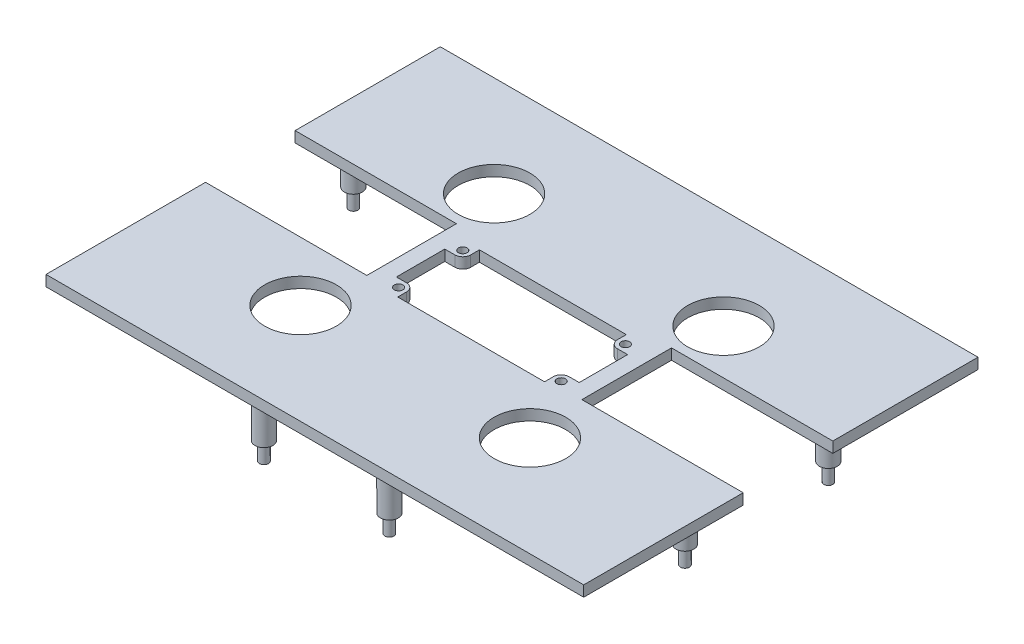
SolidWorks part; units mm, degrees
ref_plane "Front Plane" through (0, 0, 0) normal (0, 0, 1) x (1, 0, 0)
ref_plane "Top Plane" through (0, 0, 0) normal (0, 1, 0) x (1, 0, 0)
ref_plane "Right Plane" through (0, 0, 0) normal (1, 0, 0) x (0, 0, -1)
sketch "Sketch2" plane through (0, 0, 0) normal (0, 1, 0) x (1, 0, 0)
  line L1 (-75, 55) -> (75, 55)
  line L2 (-75, 55) -> (-75, -55)
  line L3 (-75, -55) -> (75, -55)
  line L4 (75, 55) -> (75, -55)
  line L5 (-75, 55) -> (75, -55) construction
  line L6 (-75, -55) -> (75, 55) construction
  point P0 (0, 0)
  dimension "D1" = 150
  dimension "D2" = 110
extrude "Boss-Extrude1" add sketch "Sketch2" against normal blind 3
sketch "Sketch3" plane through (0, -3, 0) normal (0, -1, 0) x (1, 0, 0)
  circle A0 centre (-17.5, 51.7) radius 2.5
  circle A1 centre (17.5, 51.7) radius 2.5
  circle A2 centre (66.25, 18) radius 2.5
  circle A3 centre (66.25, -22) radius 2.5
  circle A4 centre (-66.25, 18) radius 2.5
  circle A5 centre (-66.25, -22) radius 2.5
  point P12 (0, 0)
  point P14 (0, 0)
  point P15 (0, 0)
  point P16 (0, 0)
  point P17 (-66.25, 15.2285)
  point P18 (0, 0)
  dimension "D1" = 5
  dimension "D2" = 22
  dimension "D3" = 66.25
  dimension "D4" = 66.25
  dimension "D5" = 40
  dimension "D6" = 35
  dimension "D7" = 17.5
  dimension "D8" = 33.7
extrude "Boss-Extrude2" add sketch "Sketch3" along normal blind 10
sketch "Sketch4" plane through (0, -13, 0) normal (0, -1, 0) x (1, 0, 0)
  circle A0 centre (17.5, 51.7) radius 1.25
  circle A1 centre (-17.5, 51.7) radius 1.25
  circle A2 centre (-66.25, 18) radius 1.25
  circle A3 centre (-66.25, -22) radius 1.25
  circle A4 centre (66.25, -22) radius 1.25
  circle A5 centre (66.25, 18) radius 1.25
  dimension "D1" = 2.5
extrude "Boss-Extrude3" add sketch "Sketch4" along normal blind 5
sketch "Sketch5" plane through (0, 0, 0) normal (0, 1, 0) x (1, 0, 0)
  line L0 (-66.25, 22) -> (-66.25, -18) construction
  line L1 (-75, 55) -> (-75, -55) construction
  line L2 (-75, 14.5) -> (-30, 14.5)
  line L3 (-75, 14.5) -> (-75, -10.5)
  line L4 (-75, -10.5) -> (-30, -10.5)
  line L5 (-30, 14.5) -> (-30, -10.5)
  line L6 (0, -9.9) -> (0, 9.9) construction
  line L7 (75, -10.5) -> (30, -10.5)
  line L8 (30, 14.5) -> (30, -10.5)
  line L9 (75, 14.5) -> (30, 14.5)
  line L10 (75, 14.5) -> (75, -10.5)
  point P10 (-30, 2)
  point P11 (-66.25, 2)
  dimension "D1" = 45
  dimension "D2" = 25
extrude "Cut-Extrude1" cut sketch "Sketch5" against normal up to surface (3 mm away) up to face at (-66.25, -3, 20.5)
sketch "Sketch6" plane through (0, 0, 0) normal (0, 1, 0) x (1, 0, 0)
  line L0 (-32, 27) -> (-32, -27) construction
  line L3 (-30, -10.5) -> (-30, 14.5) construction
  line L4 (0, -9.9) -> (0, 9.9) construction
  circle A0 centre (-32, 27) radius 10
  circle A1 centre (-32, -27) radius 10
  circle A2 centre (32, -27) radius 10
  circle A3 centre (32, 27) radius 10
  point P0 (-27, 31.4432)
  point P1 (-27, 66.675)
  point P2 (-27, 16.9877)
  point P3 (-27, -60.2291)
  point P4 (-27, -34.714)
  point P5 (-27, 67.615)
  point P12 (-32, 0)
  dimension "D2" = 20
  dimension "D1" = 2
  dimension "D3" = 27
extrude "Cut-Extrude2" cut sketch "Sketch6" against normal up to surface (3 mm away) up to face at (-66.25, -3, 20.5)
sketch "Sketch7" plane through (0, 0, 0) normal (0, 1, 0) x (1, 0, 0)
  line L0 (-22.68, 8.95) -> (-22.68, -8.95) construction
  line L1 (-20.48, 11.4) -> (20.48, 11.4)
  line L2 (-25.5, 6.75) -> (-25.5, -6.75)
  line L3 (-20.48, -11.4) -> (20.48, -11.4)
  line L4 (25.5, 6.75) -> (25.5, -6.75)
  line L5 (-75, -10.5) -> (-75, -55) construction
  line L6 (-75, -10.5) -> (-30, -10.5) construction
  line L7 (-22.68, -8.95) -> (22.68, -8.95) construction
  line L8 (20.48, -8.95) -> (20.48, -11.4)
  line L9 (22.68, -6.75) -> (25.5, -6.75)
  line L10 (22.68, 6.75) -> (25.5, 6.75)
  line L11 (20.48, 8.95) -> (20.48, 11.4)
  line L12 (-22.68, 6.75) -> (-25.5, 6.75)
  line L13 (-20.48, 8.95) -> (-20.48, 11.4)
  line L14 (-22.68, -6.75) -> (-25.5, -6.75)
  line L15 (-20.48, -8.95) -> (-20.48, -11.4)
  circle A0 centre (-22.68, 8.95) radius 1.2
  circle A1 centre (22.68, 8.95) radius 1.2
  circle A2 centre (22.68, -8.95) radius 1.2
  circle A3 centre (-22.68, -8.95) radius 1.2
  arc A4 (-20.48, -8.95) -> (-22.68, -6.75) centre (-22.68, -8.95) ccw
  arc A5 (-22.68, 6.75) -> (-20.48, 8.95) centre (-22.68, 8.95) ccw
  arc A6 (20.48, 8.95) -> (22.68, 6.75) centre (22.68, 8.95) ccw
  arc A7 (22.68, -6.75) -> (20.48, -8.95) centre (22.68, -8.95) ccw
  circle A8 centre (-22.68, -8.95) radius 2.2 construction
  circle A9 centre (22.68, -8.95) radius 2.2 construction
  circle A10 centre (-22.68, 8.95) radius 2.2 construction
  circle A11 centre (22.68, 8.95) radius 2.2 construction
  point P0 (0, 0)
  point P14 (0, -8.95)
  point P15 (-22.68, 0)
  point P25 (0, -11.4)
  point P36 (-20.48, -11.4)
  point P41 (20.48, 11.4)
  point P44 (25.5, 0)
  point P45 (-25.5, 0)
  dimension "D3" = 2.4
  dimension "D1" = 11.4
  dimension "D2" = 22.8
  dimension "D4" = 45.36
  dimension "D5" = 17.9
  dimension "D10" = 25.5
  dimension "D11" = 25.5
  dimension "D6" = 1
  dimension "D7" = 1
  dimension "D8" = 1
  dimension "D9" = 1
extrude "Cut-Extrude3" cut sketch "Sketch7" against normal up to surface (3 mm away) up to face at (32, -3, -17)
